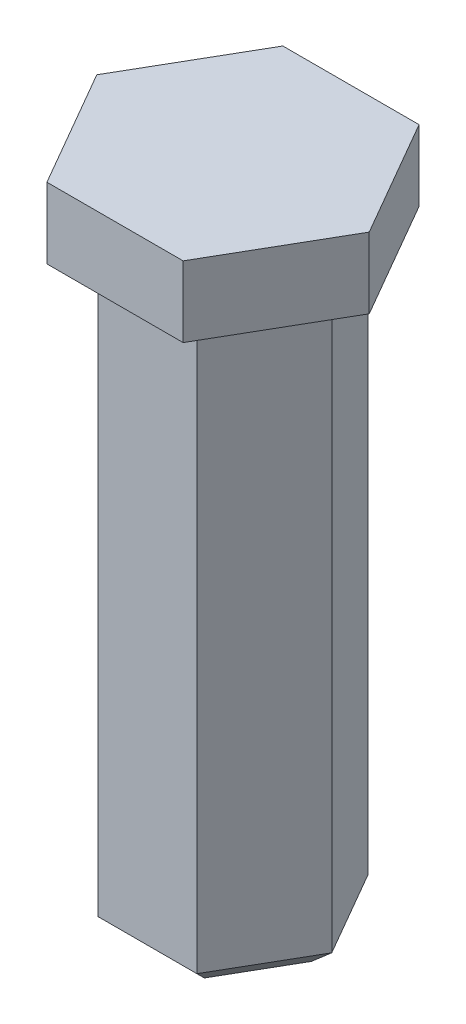
SolidWorks part; units mm, degrees
ref_plane "Front Plane" through (0, 0, 0) normal (0, 0, 1) x (1, 0, 0)
ref_plane "Top Plane" through (0, 0, 0) normal (0, 1, 0) x (1, 0, 0)
ref_plane "Right Plane" through (0, 0, 0) normal (1, 0, 0) x (0, 0, -1)
sketch "Sketch1" plane through (0, 0, 0) normal (0, 1, 0) x (1, 0, 0)
  line L1 (1.6743, 0) -> (0.8372, 1.45)
  line L2 (0.8372, 1.45) -> (-0.8372, 1.45)
  line L3 (-0.8372, 1.45) -> (-1.6743, 0)
  line L4 (-1.6743, 0) -> (-0.8372, -1.45)
  line L5 (-0.8372, -1.45) -> (0.8372, -1.45)
  line L6 (0.8372, -1.45) -> (1.6743, 0)
  circle A0 centre (0, 0) radius 1.45 construction
  dimension "D1" = 2.9
extrude "Boss-Extrude1" add sketch "Sketch1" along normal blind 10
sketch "Sketch2" plane through (0, 10, 0) normal (0, 1, 0) x (1, 0, 0)
  line L1 (2.3094, 0) -> (1.1547, 2)
  line L2 (1.1547, 2) -> (-1.1547, 2)
  line L3 (-1.1547, 2) -> (-2.3094, 0)
  line L4 (-2.3094, 0) -> (-1.1547, -2)
  line L5 (-1.1547, -2) -> (1.1547, -2)
  line L6 (1.1547, -2) -> (2.3094, 0)
  circle A0 centre (0, 0) radius 2 construction
  dimension "D1" = 4
extrude "Boss-Extrude2" add sketch "Sketch2" along normal blind 1.2
chamfer "Chamfer1" distance 0.3 angle 45 6 edges at (1.2557, 0, -0.725) (0, 0, -1.45) (-1.2557, 0, -0.725) (-1.2557, 0, 0.725) (0, 0, 1.45) (1.2557, 0, 0.725)
